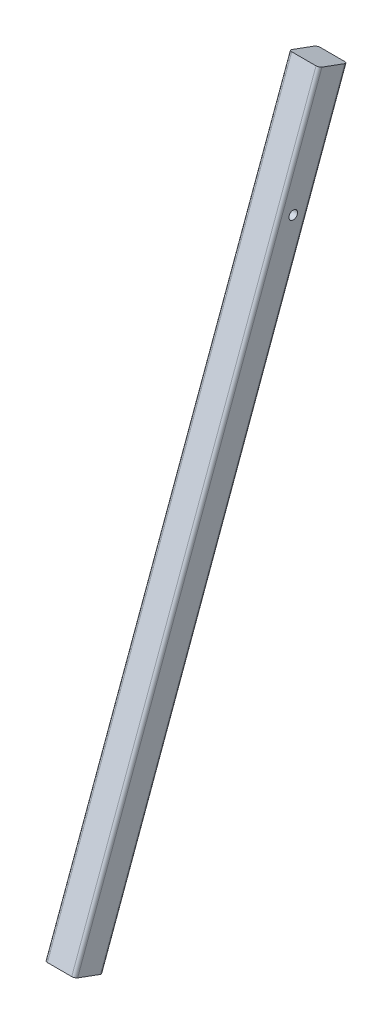
SolidWorks part; units mm, degrees
ref_plane "Front Plane" through (0, 0, 0) normal (0, 0, 1) x (1, 0, 0)
ref_plane "Top Plane" through (0, 0, 0) normal (0, 1, 0) x (1, 0, 0)
ref_plane "Right Plane" through (0, 0, 0) normal (1, 0, 0) x (0, 0, -1)
ref_plane "Plane1" through (0, 581.9411, 1587.9102) normal (0, 0.3441, 0.9389) x (-1, 0, 0)
sketch "Sketch1" plane through (0, 581.9411, 1587.9102) normal (0, 0.3441, 0.9389) x (-1, 0, 0)
  line L0 (28.6909, 626.6562) -> (-1.3091, 626.6562)
  line L1 (-1.3091, 626.6562) -> (-1.3091, -73.3438)
  line L2 (-1.3091, -73.3438) -> (28.6909, -73.3438)
  line L3 (28.6909, -73.3438) -> (28.6909, 626.6562)
  dimension "D1" = 700
  dimension "D2" = 30
extrude "Boss-Extrude1" add sketch "Sketch1" against normal blind 30
hole_wizard "Ø8.5 (8.5) Diameter Hole1" positions "Sketch3" profile "Sketch2" hole size "Ø8.5" standard "ANSI Metric" end condition through all
sketch "Sketch3" plane through (1.3091, 0, 0) normal (1, 0, 0) x (0, 0, -1)
  line L1 (-1534.5045, 640.4828) -> (-1562.6724, 650.8059) construction
  point P0 (-1588.1602, 537.6672)
  dimension "D1" = 115
sketch "Sketch2" plane through (1.3091, 537.6672, 1588.1602) normal (0, 1, 0) x (0, 0, -1)
  line L0 (0, 0) -> (0, 30)
  line L1 (0, 30) -> (4.25, 30)
  line L2 (4.25, 30) -> (4.25, 0)
  line L5 (4.25, 0) -> (0, 0)
  line L11 (0, -6.35) -> (0, 107.95) construction
  dimension "Thru Hole Dia." = 8.5
  dimension "Thru Hole Depth" = 30
fillet "Fillet1" radius 3 4 edges at (-28.6909, 322.1796, 1683.1082) (1.3091, 322.1796, 1683.1082) (-28.6909, 311.8566, 1654.9402) (1.3091, 311.8566, 1654.9402)
